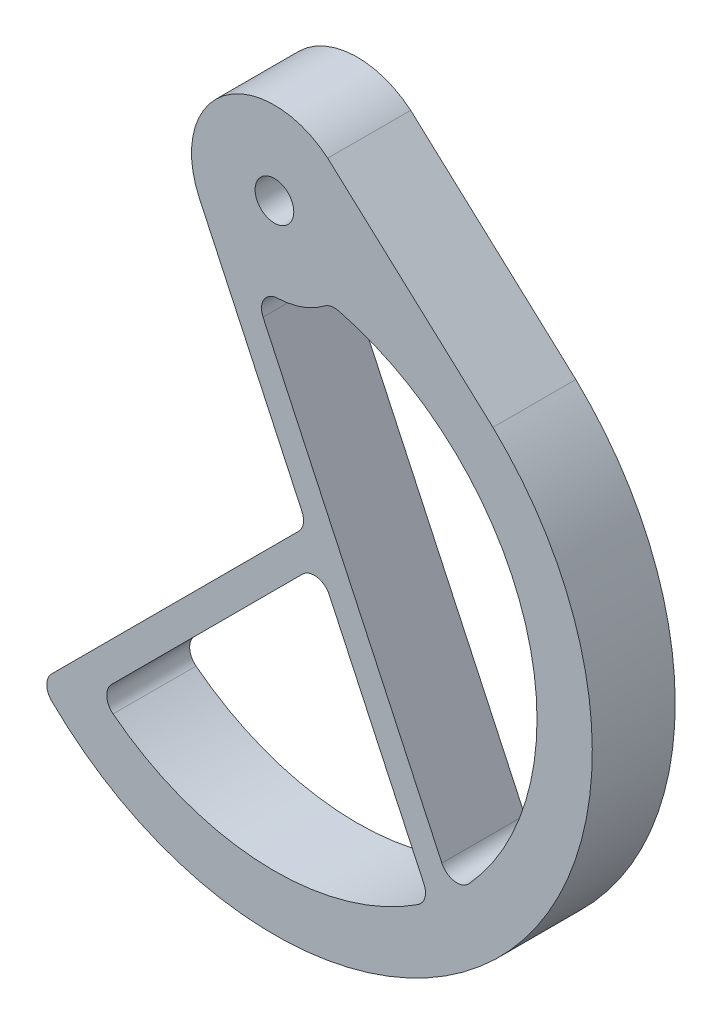
SolidWorks part; units mm, degrees
material "ABS"
ref_plane "正面" through (0, 0, 0) normal (0, 0, 1) x (1, 0, 0)
ref_plane "平面" through (0, 0, 0) normal (0, 1, 0) x (1, 0, 0)
ref_plane "右側面" through (0, 0, 0) normal (1, 0, 0) x (0, 0, -1)
sketch "ｽｹｯﾁ1" plane through (0, 0, 0) normal (0, 0, 1) x (1, 0, 0)
  line L1 (9.9336, 0.7043) -> (27.0462, -35.9938)
  line L2 (9.6418, 68.9907) -> (39.5241, 41.7624)
  line L4 (4.3888, 7.9244) -> (-40.3035, -36.7679)
  line L5 (5.0933, 1.5578) -> (-29.4572, -32.9928)
  line L6 (-13.5946, 51.1607) -> (4.9864, 11.3135)
  line L7 (30.2877, -31.1143) -> (-2.0547, 38.2444)
  arc A0 (-40.2839, -41.0299) -> (37.9168, 43.2269) centre (0, 0) ccw
  arc A1 (-29.1788, -37.4813) -> (25.9673, -39.7737) centre (0, 0) ccw
  arc A2 (0.5535, 42.5102) -> (9.0577, 45.5435) centre (0, 57.5) ccw
  arc A3 (35.2318, -31.8586) -> (11.602, 46.0613) centre (0, 0) ccw
  arc A4 (10.5469, 68.1659) -> (-13.5946, 51.1607) centre (0, 57.5) ccw
  arc A5 (-40.3035, -36.7679) -> (-40.2839, -41.0299) centre (-38.1821, -38.8893) ccw
  arc A6 (-29.4572, -32.9928) -> (-29.1788, -37.4813) centre (-27.3359, -35.1141) ccw
  arc A7 (27.0462, -35.9938) -> (25.9673, -39.7737) centre (24.3273, -37.2617) cw
  arc A8 (5.0933, 1.5578) -> (9.9336, 0.7043) centre (7.2147, -0.5635) cw
  arc A9 (35.2318, -31.8586) -> (30.2877, -31.1143) centre (33.0067, -29.8464) cw
  arc A10 (4.9864, 11.3135) -> (4.3888, 7.9244) centre (2.2675, 10.0457) cw
  arc A11 (-2.0547, 38.2444) -> (0.5535, 42.5102) centre (0.6642, 39.5123) cw
  arc A12 (11.602, 46.0613) -> (9.0577, 45.5435) centre (10.8692, 43.1522) ccw
  point P24 (8.1229, 4.5874)
  dimension "D1" = 3
  dimension "D2" = 3
  dimension "D3" = 3
  dimension "D4" = 3
  dimension "D5" = 3
  dimension "D6" = 3
  dimension "D7" = 3
  dimension "D8" = 3
extrude "ﾎﾞｽ - 押し出し1" add sketch "ｽｹｯﾁ1" along normal blind 15 contours L6 A10 L4 A5 A0 L2 A4 A12 A3 A9 L7 A11 A2 L5 A8 L1 A7 A1 A6
sketch "ｽｹｯﾁ6" plane through (0, 0, 15) normal (0, 0, 1) x (1, 0, 0)
  circle A0 centre (0, 57.5) radius 3.5
extrude "ｶｯﾄ - 押し出し2" cut sketch "ｽｹｯﾁ6" against normal blind 15
sketch "ｽｹｯﾁ8" plane through (0, 0, 0) normal (0, 0, -1) x (-1, 0, 0)
  circle A0 centre (0, 57.5) radius 10.1
extrude "ｶｯﾄ - 押し出し4" cut sketch "ｽｹｯﾁ8" against normal blind 2
